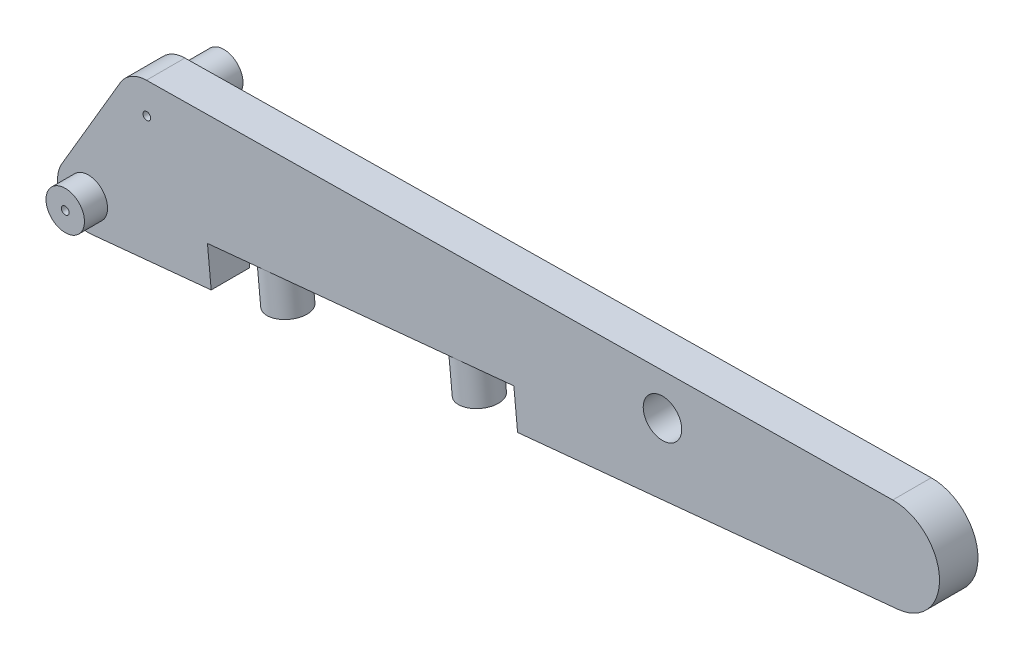
SolidWorks part; units mm, degrees
material "ABS"
ref_plane "Front Plane" through (0, 0, 0) normal (0, 0, 1) x (1, 0, 0)
ref_plane "Top Plane" through (0, 0, 0) normal (0, 1, 0) x (1, 0, 0)
ref_plane "Right Plane" through (0, 0, 0) normal (1, 0, 0) x (0, 0, -1)
sketch "Sketch2" plane through (0, 0, 0) normal (0, 0, 1) x (1, 0, 0)
  line L0 (-7.5998, -12.9323) -> (0, 0)
  line L1 (0, 0) -> (97, -0.7468)
  dimension "D1" = 97
  dimension "D2" = 15
  dimension "D3" = 120
sketch "Sketch3" plane through (0, 0, 0) normal (0, 0, 1) x (1, 0, 0)
  line L0 (-11.0484, -10.9056) -> (-3.4486, 2.0266)
  line L1 (-0.0517, 3.9997) -> (96.9225, 5.2527)
  line L2 (97.581, -6.7186) -> (-7.2125, -16.9135)
  circle A0 centre (-7.5998, -12.9323) radius 2.5
  arc A1 (-11.0484, -10.9056) -> (-7.2125, -16.9135) centre (-7.5998, -12.9323) ccw
  circle A2 centre (0, 0) radius 2.5
  arc A3 (-0.0517, 3.9997) -> (-3.4486, 2.0266) centre (0, 0) ccw
  arc A4 (97.581, -6.7186) -> (96.9225, 5.2527) centre (97, -0.7468) ccw
  dimension "D1" = 5
  dimension "D2" = 8
  dimension "D3" = 5
  dimension "D4" = 8
  dimension "D5" = 12
extrude "Boss-Extrude1" add sketch "Sketch3" along normal blind 5
sketch "Sketch4" plane through (0, 0, 5) normal (0, 0, 1) x (1, 0, 0)
  circle A0 centre (0, 0) radius 2.5
  circle A1 centre (0, 0) radius 0.5
  dimension "D1" = 1
  dimension "D2" = 5
extrude "Boss-Extrude2" add sketch "Sketch4" against normal blind 10
sketch "Sketch5" plane through (0, 0, 0) normal (0, 0, -1) x (-1, 0, 0)
  circle A0 centre (7.5998, -12.9323) radius 2.5
  circle A1 centre (7.5998, -12.9323) radius 0.5
  dimension "D1" = 1
  dimension "D2" = 5
extrude "Boss-Extrude3" add sketch "Sketch5" against normal blind 8
sketch "Sketch6" plane through (0, 0, 0) normal (0, 0, -1) x (-1, 0, 0)
  line L0 (0, 0) -> (-97, -0.7468) construction
  circle A1 centre (-67, -0.5158) radius 2.5
  dimension "D1" = 5
  dimension "D2" = 30
extrude "Cut-Extrude1" cut sketch "Sketch6" against normal blind 5
sketch "Sketch7" plane through (0, 0, 0) normal (0, 0, -1) x (-1, 0, 0)
  line L0 (-48.1755, -11.525) -> (-8.3635, -15.3981)
  line L1 (-48.1755, -11.525) -> (-47.6891, -6.525)
  line L2 (-8.3635, -15.3981) -> (-7.877, -10.3981)
  line L3 (-47.6891, -6.525) -> (-7.877, -10.3981)
  line L4 (7.2125, -16.9135) -> (-97.581, -6.7186) construction
  dimension "D1" = 50
  dimension "D2" = 5
  dimension "D3" = 40
extrude "Cut-Extrude2" cut sketch "Sketch7" against normal blind 5
sketch "Sketch8" plane through (1.076, -11.0598, 0) normal (0.0968, -0.9953, 0) x (0.9953, 0.0968, 0)
  line L0 (6.8332, 0) -> (46.8332, 0) construction
  line L1 (46.8332, 5) -> (46.8332, 0) construction
  line L2 (6.8332, 5) -> (6.8332, 0) construction
  circle A0 centre (14.3332, 2.5) radius 2.5
  circle A1 centre (14.3332, 2.5) radius 0.5
  circle A2 centre (39.3332, 2.5) radius 0.5
  circle A3 centre (39.3332, 2.5) radius 2.5
  point P8 (0, 0)
  dimension "D1" = 5
  dimension "D2" = 1
  dimension "D6" = 1
  dimension "D7" = 5
  dimension "D3" = 2.5
  dimension "D4" = 7.5
  dimension "D5" = 2.5
  dimension "D8" = 7.5
extrude "Boss-Extrude4" add sketch "Sketch8" along normal blind 5
